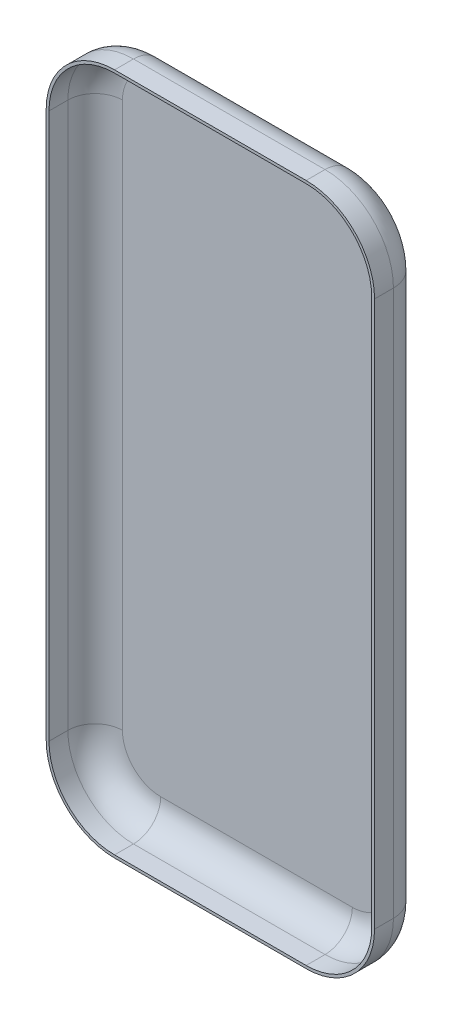
SolidWorks part; units mm, degrees
ref_plane "Front" through (0, 0, 0) normal (0, 0, 1) x (1, 0, 0)
ref_plane "Top" through (0, 0, 0) normal (0, 1, 0) x (1, 0, 0)
ref_plane "Right" through (0, 0, 0) normal (1, 0, 0) x (0, 0, -1)
sketch "Sketch1" plane through (0, 0, 0) normal (0, 0, 1) x (1, 0, 0)
  line L0 (-23.8379, -68.834) -> (23.8379, -68.834)
  line L1 (23.8379, -68.834) -> (23.8379, 0)
  line L2 (23.8379, 0) -> (-23.8379, 0)
  line L3 (-23.8379, 0) -> (-23.8379, -68.834)
  dimension "D1" = 47.6758
  dimension "D2" = 68.834
extrude "Boss-Extrude1" add sketch "Sketch1" against normal blind 7.112
sketch "Sketch11" plane through (0, 0, 0) normal (0, 1, 0) x (1, 0, 0)
  line L4 (-23.8379, 0) -> (23.8379, 0)
  line L5 (23.8379, 0) -> (23.8379, 7.112)
  line L6 (23.8379, 7.112) -> (-23.8379, 7.112)
  line L7 (-23.8379, 7.112) -> (-23.8379, 0)
  line L8 (-23.8379, 0) -> (23.8379, 0)
  line L9 (23.8379, 0) -> (23.8379, 7.112)
  line L10 (23.8379, 7.112) -> (-23.8379, 7.112)
  line L11 (-23.8379, 7.112) -> (-23.8379, 0)
  dimension "D1" = 0
extrude "Boss-Extrude2" add sketch "Sketch11" along normal blind 30.2768
fillet "Fillet3" radius 9.9314 4 edges at (-23.8379, -68.834, -3.556) (23.8379, -68.834, -3.556) (23.8379, 30.2768, -3.556) (-23.8379, 30.2768, -3.556)
fillet "Fillet6" radius 4.3688 7 edges at (-23.8379, -19.2786, -7.112) (-20.9291, -65.9252, -7.112) (0, -68.834, -7.112) (23.8379, -19.2786, -7.112) (-20.9291, 27.368, -7.112) (0, 30.2768, -7.112) (20.9291, 27.368, -7.112)
shell "Shell1" thickness 0.4064
sketch "Sketch12" plane through (0, 0, 0) normal (0, 0, 1) x (1, 0, 0)
  line L1 (33.0381, 0) -> (-33.0381, 0)
  line L2 (33.0381, 0) -> (33.0381, 35.7406)
  line L3 (33.0381, 35.7406) -> (-33.0381, 35.7406)
  line L4 (-33.0381, 0) -> (-33.0381, 35.7406)
extrude "Cut-Extrude9" [suppressed] cut sketch "Sketch12" against normal through all
sketch "Sketch2" plane through (0, 0, -7.112) normal (0, 0, -1) x (-1, 0, 0)
  line L0 (0, 0) -> (0, -68.834) construction
  line L2 (13.7926, -15.8987) -> (13.7926, -8.949) construction
  line L3 (-13.7926, -23.8005) -> (-13.7926, -8.949) construction
  line L5 (13.7926, -8.949) -> (-13.7926, -8.949) construction
  line L6 (0, -8.949) -> (0, -7.1987)
  circle A0 centre (-3.9957, -23.8005) radius 9.7379 construction
  circle A1 centre (-2.0026, -25.7405) radius 9.7142 construction
  circle A2 centre (0.5083, -22.2188) radius 9.734 construction
  circle A3 centre (0.5083, -22.2188) radius 9.7929
  circle A4 centre (-3.9957, -23.8005) radius 9.7969
  circle A5 centre (-2.0026, -25.7405) radius 9.7731
  circle A6 centre (0.5083, -22.2188) radius 9.6751
  circle A7 centre (-3.9957, -23.8005) radius 9.679
  circle A8 centre (-2.0026, -25.7405) radius 9.6553
  ellipse E0 centre (-2.4998, -18.2268) end of major axis (-3.1675, -16.3788) minor radius 0.8992
  spline S0 degree 3 poles (-2.7888, -22.7193) (-2.9522, -22.7062) (-3.6232, -22.6523) (-5.2777, -21.5181) (-7.4795, -19.0172) (-9.5894, -16.1686) (-10.8831, -14.2895) (-11.2683, -13.7301) knots 0 0 0 0 0.038746 0.159165 0.456538 0.838188 1 1 1 1
  spline S1 degree 3 poles (-11.2683, -13.7301) (-10.7339, -15.1306) (-9.7342, -17.7506) (-8.2411, -21.0782) (-7.1032, -23.5106) (-6.2066, -25.8) (-5.413, -28.2793) (-4.8286, -30.9113) (-4.7098, -33.079) (-4.8287, -34.9625) (-4.9844, -36.2168) (-5.0717, -36.9194) knots 0 0 0 0 0.184277 0.34472 0.44833 0.514374 0.646889 0.76821 0.844599 0.912963 1 1 1 1
  spline S2 degree 3 poles (-2.7888, -22.7193) (-2.799, -23.1492) (-2.8194, -24.0094) (-2.7947, -25.4618) (-2.9317, -27.3534) (-3.2362, -30.0014) (-3.7056, -32.5731) (-4.343, -34.86) (-4.7098, -36.1089) (-5.0214, -36.8066) (-5.0717, -36.9194) knots 0 0 0 0 0.089159 0.178378 0.301029 0.481936 0.731085 0.841626 0.974408 1 1 1 1
  spline S3 degree 3 poles (-2.331, -22.7193) (-2.1638, -22.704) (-1.7259, -22.664) (-0.0885, -22.1403) (2.3865, -21.4275) (5.3204, -20.2469) (7.7115, -19.1407) (9.7474, -18.0627) (11.7388, -16.9856) (13.0774, -16.2772) (13.7926, -15.8987) knots 0 0 0 0 0.028588 0.074865 0.292017 0.468865 0.613602 0.74155 0.861906 1 1 1 1
  spline S4 degree 3 poles (13.7926, -15.8987) (13.3829, -16.2758) (12.5599, -17.0333) (11.3584, -18.2265) (10.1731, -19.5205) (8.9893, -20.7469) (7.8492, -22.0172) (6.8502, -23.0904) (5.9713, -24.0693) (4.177, -26.2392) (2.3676, -28.5964) (0.4602, -31.1761) (-0.5275, -32.6048) (-1.5804, -34.223) (-2.6935, -36.0626) (-3.7216, -37.8448) (-4.533, -39.5303) (-5.1522, -41.0331) (-5.664, -42.3954) (-6.0441, -43.4306) (-6.2764, -44.1041) (-6.4631, -44.6182) (-6.6075, -45.047) (-6.7623, -45.3603) (-6.8896, -45.5422) (-7.0454, -45.6699) (-7.2125, -45.6385) (-7.3723, -45.5757) (-7.4022, -45.3472) (-7.244, -45.0712) (-7.0647, -44.4416) (-6.7107, -43.545) (-6.3044, -42.2344) (-5.8263, -40.8573) (-5.3029, -39.257) (-4.7492, -37.462) (-4.0803, -35.2975) (-3.4748, -32.8843) (-2.9877, -30.6306) (-2.6846, -28.8017) (-2.4111, -26.8662) (-2.3156, -24.8886) (-2.3267, -23.3225) (-2.331, -22.7193) knots 0 0 0 0 0.027582 0.055408 0.083848 0.114504 0.139838 0.168396 0.18714 0.204997 0.307861 0.334295 0.363922 0.39389 0.429916 0.470438 0.495748 0.522521 0.550927 0.567837 0.577148 0.58622 0.594931 0.599565 0.603406 0.606057 0.60882 0.611422 0.613815 0.618972 0.626943 0.646168 0.666698 0.694884 0.718383 0.7501 0.787942 0.830589 0.873307 0.902128 0.92241 0.970112 1 1 1 1
sketch "Sketch3" plane through (0, 0, -7.112) normal (0, 0, -1) x (-1, 0, 0)
  line L0 (0, 0) -> (0, -74.6728) construction
  line L2 (-6.2093, -52.5207) -> (6.2093, -52.5207) construction
  line L3 (13.9065, -68.834) -> (-13.9065, -68.834) construction
  text T0 "PM1" font "SansSerif" height 4.445
  point P9 (0, -52.5207)
  dimension "D1" = 12.4185
  dimension "D2" = 16.3133
sketch "Sketch4" plane through (0, 0, -7.112) normal (0, 0, -1) x (-1, 0, 0)
  line L0 (13.9065, -68.834) -> (-13.9065, -68.834) construction
  line L1 (23.8379, 20.3454) -> (23.8379, -58.9026) construction
  text T0 "TM" font "Microsoft Sans Serif" height 1.524
  dimension "D1" = 19.4407
  dimension "D2" = 17.2888
sketch "Sketch6" plane through (0, 0, -7.112) normal (0, 0, -1) x (-1, 0, 0)
  line L0 (0, 0) -> (0, -70.1655) construction
  line L2 (8.5071, -57.2832) -> (-8.5071, -57.2832) construction
  line L3 (-6.2093, -52.5207) -> (6.2093, -52.5207) construction
  text T0 "111111" font "SansSerif" height 2.794
  point P8 (0, -57.2832)
  dimension "D1" = 4.7625
sketch "Sketch7" [suppressed] plane through (0, 0, -7.112) normal (0, 0, -1) x (-1, 0, 0)
  line L0 (-12.6678, -3.175) -> (-17.8122, -3.175) construction
  line L4 (-15.24, -3.175) -> (-15.24, 1.9835) construction
  line L6 (19.4691, 0) -> (-19.4691, 0) construction
  line L7 (0, -7.3784) -> (0, 0) construction
  line L12 (12.6678, -3.175) -> (17.8122, -3.175) construction
  line L13 (15.24, -3.175) -> (15.24, 1.9835) construction
  text T0 "N\r\n" font "SansSerif" height 2.286
  text T3 "N" font "SansSerif" height 2.286
  dimension "D1" = 3.175
  dimension "D2" = 15.24
extrude "Cut-Extrude1" [suppressed] cut sketch "Sketch2" against normal blind 0.0254
sketch "Sketch8" plane through (0, 0, -7.112) normal (0, 0, -1) x (-1, 0, 0)
  ellipse E0 centre (-2.4998, -18.2268) end of major axis (-3.1675, -16.3788) minor radius 0.8992 construction
  ellipse E1 centre (-2.4998, -18.2268) end of major axis (-3.1675, -16.3788) minor radius 0.8992
  spline S0 degree 3 poles (348.7957, -1991.3331) (-26.869, 13.2954) (-10.1093, -25.3455) (-0.0885, -22.1403) (2.3865, -21.4275) (5.3204, -20.2469) (7.7115, -19.1407) (9.7474, -18.0627) (68.3963, 13.6603) (138.9376, 22.0457) (-769.2553, 1820.9044) knots -1.495062 -1.495062 -1.495062 -1.495062 0.028588 0.074865 0.292017 0.468865 0.613602 0.74155 0.861906 11.993594 11.993594 11.993594 11.993594 only from (-2.331, -22.7193) to (13.7926, -15.8987) construction
  spline S1 degree 3 poles (-1281.5828, 1506.7857) (84.2392, 1.6902) (35.2708, 5.5205) (11.3584, -18.2265) (10.1731, -19.5205) (8.9893, -20.7469) (7.8492, -22.0172) (6.8502, -23.0904) (5.9713, -24.0693) (4.177, -26.2392) (2.3676, -28.5964) (0.4602, -31.1761) (-0.5275, -32.6048) (-1.5804, -34.223) (-2.6935, -36.0626) (-3.7216, -37.8448) (-4.533, -39.5303) (-5.1522, -41.0331) (-5.664, -42.3954) (-6.0441, -43.4306) (-6.2764, -44.1041) (-6.4631, -44.6182) (-6.6075, -45.047) (-6.7623, -45.3603) (-6.8896, -45.5422) (-7.0454, -45.6699) (-7.2125, -45.6385) (-7.3723, -45.5757) (-7.4022, -45.3472) (-7.244, -45.0712) (-7.0647, -44.4416) (-6.7107, -43.545) (-6.3044, -42.2344) (-5.8263, -40.8573) (-5.3029, -39.257) (-4.7492, -37.462) (-4.0803, -35.2975) (-3.4748, -32.8843) (-2.9877, -30.6306) (-2.6846, -28.8017) (-2.4111, -26.8662) (-0.7491, 7.5317) (-39.952, 40.6751) (1991.9867, 115.691) knots -1.584926 -1.584926 -1.584926 -1.584926 0.027582 0.055408 0.083848 0.114504 0.139838 0.168396 0.18714 0.204997 0.307861 0.334295 0.363922 0.39389 0.429916 0.470438 0.495748 0.522521 0.550927 0.567837 0.577148 0.58622 0.594931 0.599565 0.603406 0.606057 0.60882 0.611422 0.613815 0.618972 0.626943 0.646168 0.666698 0.694884 0.718383 0.7501 0.787942 0.830589 0.873307 0.902128 0.92241 0.970112 2.604448 2.604448 2.604448 2.604448 only from (13.7926, -15.8987) to (-2.331, -22.7193) construction
  spline S2 degree 3 poles (-1999.289, 85.688) (31.156, 28.901) (-3.2669, 2.2739) (-2.7947, -25.4618) (-2.9317, -27.3534) (-3.2362, -30.0014) (-3.7056, -32.5731) (-4.343, -34.86) (-7.8748, -46.8867) (-34.666, -49.1177) (1841.3681, -805.1522) knots -5.447354 -5.447354 -5.447354 -5.447354 0.089159 0.178378 0.301029 0.481936 0.731085 0.841626 0.974408 3.320544 3.320544 3.320544 3.320544 only from (-2.7888, -22.7193) to (-5.0717, -36.9194) construction
  spline S3 degree 3 poles (-513.2462, -1956.3697) (23.6382, 18.3692) (2.7938, -27.0515) (-5.2777, -21.5181) (-7.4795, -19.0172) (-36.1689, 19.716) (-34.7281, 73.3823) (-1827.2691, -847.9829) knots -1.770642 -1.770642 -1.770642 -1.770642 0.038746 0.159165 0.456538 0.838188 11.592436 11.592436 11.592436 11.592436 only from (-2.7888, -22.7193) to (-11.2683, -13.7301) construction
  spline S4 degree 3 poles (-1911.7507, -629.5487) (4.0961, 105.1076) (-31.3204, 30.3595) (-8.2411, -21.0782) (-7.1032, -23.5106) (-6.2066, -25.8) (-5.413, -28.2793) (-4.8286, -30.9113) (-4.7098, -33.079) (-6.7775, -65.8398) (-58.0916, -92.4948) (1969.4314, -349.9469) knots -6.481935 -6.481935 -6.481935 -6.481935 0.184277 0.34472 0.44833 0.514374 0.646889 0.76821 0.844599 0.912963 4.799804 4.799804 4.799804 4.799804 only from (-11.2683, -13.7301) to (-5.0717, -36.9194) construction
  spline S5 degree 3 poles (-2.331, -22.7193) (-2.1638, -22.704) (-1.7259, -22.664) (-0.0885, -22.1403) (2.3865, -21.4275) (5.3204, -20.2469) (7.7115, -19.1407) (9.7474, -18.0627) (11.7388, -16.9856) (13.0774, -16.2772) (13.7926, -15.8987) knots 0 0 0 0 0.028588 0.074865 0.292017 0.468865 0.613602 0.74155 0.861906 1 1 1 1
  spline S6 degree 3 poles (13.7926, -15.8987) (13.3829, -16.2758) (12.5599, -17.0333) (11.3584, -18.2265) (10.1731, -19.5205) (8.9893, -20.7469) (7.8492, -22.0172) (6.8502, -23.0904) (5.9713, -24.0693) (4.177, -26.2392) (2.3676, -28.5964) (0.4602, -31.1761) (-0.5275, -32.6048) (-1.5804, -34.223) (-2.6935, -36.0626) (-3.7216, -37.8448) (-4.533, -39.5303) (-5.1522, -41.0331) (-5.664, -42.3954) (-6.0441, -43.4306) (-6.2764, -44.1041) (-6.4631, -44.6182) (-6.6075, -45.047) (-6.7623, -45.3603) (-6.8896, -45.5422) (-7.0454, -45.6699) (-7.2125, -45.6385) (-7.3723, -45.5757) (-7.4022, -45.3472) (-7.244, -45.0712) (-7.0647, -44.4416) (-6.7107, -43.545) (-6.3044, -42.2344) (-5.8263, -40.8573) (-5.3029, -39.257) (-4.7492, -37.462) (-4.0803, -35.2975) (-3.4748, -32.8843) (-2.9877, -30.6306) (-2.6846, -28.8017) (-2.4111, -26.8662) (-2.3156, -24.8886) (-2.3267, -23.3225) (-2.331, -22.7193) knots 0 0 0 0 0.027582 0.055408 0.083848 0.114504 0.139838 0.168396 0.18714 0.204997 0.307861 0.334295 0.363922 0.39389 0.429916 0.470438 0.495748 0.522521 0.550927 0.567837 0.577148 0.58622 0.594931 0.599565 0.603406 0.606057 0.60882 0.611422 0.613815 0.618972 0.626943 0.646168 0.666698 0.694884 0.718383 0.7501 0.787942 0.830589 0.873307 0.902128 0.92241 0.970112 1 1 1 1
  spline S7 degree 3 poles (-2.7888, -22.7193) (-2.799, -23.1492) (-2.8194, -24.0094) (-2.7947, -25.4618) (-2.9317, -27.3534) (-3.2362, -30.0014) (-3.7056, -32.5731) (-4.343, -34.86) (-4.7098, -36.1089) (-5.0214, -36.8066) (-5.0717, -36.9194) knots 0 0 0 0 0.089159 0.178378 0.301029 0.481936 0.731085 0.841626 0.974408 1 1 1 1
  spline S8 degree 3 poles (-2.7888, -22.7193) (-2.9522, -22.7062) (-3.6232, -22.6523) (-5.2777, -21.5181) (-7.4795, -19.0172) (-9.5894, -16.1686) (-10.8831, -14.2895) (-11.2683, -13.7301) knots 0 0 0 0 0.038746 0.159165 0.456538 0.838188 1 1 1 1
  spline S9 degree 3 poles (-11.2683, -13.7301) (-10.7339, -15.1306) (-9.7342, -17.7506) (-8.2411, -21.0782) (-7.1032, -23.5106) (-6.2066, -25.8) (-5.413, -28.2793) (-4.8286, -30.9113) (-4.7098, -33.079) (-4.8287, -34.9625) (-4.9844, -36.2168) (-5.0717, -36.9194) knots 0 0 0 0 0.184277 0.34472 0.44833 0.514374 0.646889 0.76821 0.844599 0.912963 1 1 1 1
extrude "Cut-Extrude2" [suppressed] cut sketch "Sketch8" against normal blind 0.0508
extrude "Cut-Extrude3" [suppressed] cut sketch "Sketch3" against normal blind 0.0508
extrude "Cut-Extrude5" [suppressed] cut sketch "Sketch6" against normal blind 0.0508
extrude "Cut-Extrude6" [suppressed] cut sketch "Sketch7" against normal blind 0.0508
sketch "Sketch9" [suppressed] plane through (0, 0, -7.112) normal (0, 0, -1) x (-1, 0, 0)
  line L0 (11.2649, -12.1289) -> (11.2649, -59.0323) construction
  line L5 (23.8379, 0) -> (23.8379, -58.9026) construction
  text T0 "KEEP THIS SIDE DEEP" font "Microsoft Sans Serif" height in points 11
  dimension "D1" = 12.573
extrude "Cut-Extrude7" [suppressed] cut sketch "Sketch9" against normal blind 0.0508
sketch "Sketch10" [suppressed] plane through (0, 0, -7.112) normal (0, 0, -1) x (-1, 0, 0)
  line L0 (-12.6967, -9.2713) -> (-12.6967, -55.6207) construction
  line L21 (-7.5555, -9.271) -> (-17.8378, -9.271) construction
  line L23 (-12.6967, -6.2234) -> (-12.6967, -9.2713) construction
  line L32 (-7.6813, -10.506) -> (-7.6813, -61.1263) construction
  line L33 (-11.1925, -14.9119) -> (-11.1925, -56.7204) construction
  line L34 (-7.6813, -35.8161) -> (-11.1925, -35.8161) construction
  line L35 (-15.23, -10.506) -> (-15.23, -61.1263) construction
  line L36 (-7.6813, -61.1263) -> (-15.23, -61.1263) construction
  line L37 (-12.6967, -3.1754) -> (-12.6967, -6.2234) construction
  line L46 (-7.4788, -3.1845) -> (-17.3151, -3.1754) construction
  line L47 (-12.6967, -3.1754) -> (-12.6967, 1.983) construction
  line L49 (-7.5555, -6.223) -> (-17.8378, -6.223) construction
  line L50 (0, 0) -> (0, 6.2397) construction
  line L52 (7.5042, -6.4865) -> (17.7865, -6.477) construction
  line L53 (12.6967, -3.1754) -> (12.6967, 1.983) construction
  line L54 (7.4788, -3.1845) -> (17.3151, -3.1754) construction
  line L55 (12.6967, -3.1754) -> (12.6967, -6.2226) construction
  line L56 (12.6967, -6.2226) -> (12.6967, -9.2713) construction
  line L57 (7.5555, -9.271) -> (17.8378, -9.271) construction
  line L58 (-7.6813, -10.506) -> (-15.23, -10.506) construction
  text T0 "0907ABCD" font "Microsoft Sans Serif" height in points 12
  text T2 "4" font "Microsoft Sans Serif" height 2.286
  text T3 "DIAG" font "Microsoft Sans Serif" height 1.778
  text T4 "PWR" font "Microsoft Sans Serif" height 1.778
  text T5 "1" font "Microsoft Sans Serif" height 2.286
  text T6 "NET" font "Microsoft Sans Serif" height in points 10
  dimension "D2" = 3.302
  dimension "D3" = 7.5488
  dimension "D4" = 50.6202
  dimension "D5" = 32.5796
  dimension "D6" = 8.1128
extrude "Cut-Extrude8" [suppressed] cut sketch "Sketch10" against normal blind 0.0508
sketch "Sketch13" [suppressed] plane through (0, 0, -7.112) normal (0, 0, -1) x (-1, 0, 0)
  line L0 (13.8938, -68.834) -> (-13.8938, -68.834) construction
  line L1 (23.8252, -68.834) -> (-23.8252, -68.834)
  line L2 (23.8252, -68.834) -> (23.8252, 0)
  line L3 (23.8252, 0) -> (-23.8252, 0)
  line L4 (-23.8252, -68.834) -> (-23.8252, 0)
  line L5 (-23.8252, -58.9026) -> (-23.8252, 20.3454) construction
  line L6 (23.8252, 20.3454) -> (23.8252, -58.9026) construction
  dimension "D1" = 68.834
extrude "Cut-Extrude10" [suppressed] cut sketch "Sketch13" against normal through all
